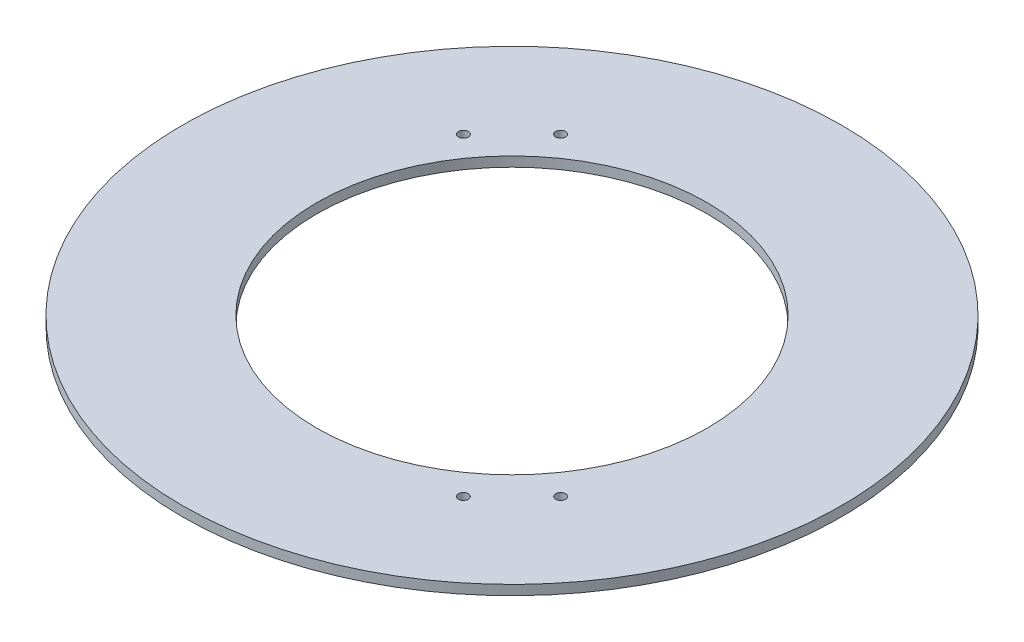
SolidWorks part; units mm, degrees
material "6061-T6 (SS)"
ref_plane "Front Plane" through (0, 0, 0) normal (0, 0, 1) x (1, 0, 0)
ref_plane "Top Plane" through (0, 0, 0) normal (0, 1, 0) x (1, 0, 0)
ref_plane "Right Plane" through (0, 0, 0) normal (1, 0, 0) x (0, 0, -1)
sketch "Sketch2" plane through (0, 0, 0) normal (0, 1, 0) x (1, 0, 0)
  line L0 (-135, 0) -> (135, 0) construction
  line L2 (0, 135) -> (0, -135) construction
  line L4 (-95.4594, 95.4594) -> (95.4594, -95.4594) construction
  line L5 (-54.3023, 74.2073) -> (-74.2073, 54.3023) construction
  line L6 (95.4594, 95.4594) -> (-95.4594, -95.4594) construction
  line L7 (74.2073, -54.3023) -> (54.3023, -74.2073) construction
  circle A0 centre (0, 0) radius 80
  circle A1 centre (0, 0) radius 135
  circle A6 centre (-74.2073, 54.3023) radius 2
  circle A7 centre (-54.3023, 74.2073) radius 2
  circle A8 centre (54.3023, -74.2073) radius 2
  circle A9 centre (74.2073, -54.3023) radius 2
  dimension "D1" = 160
  dimension "D2" = 270
  dimension "D3" = 181.74
  dimension "D7" = 4
  dimension "D6" = 45
  dimension "D8" = 45
  dimension "D9" = 28.15
extrude "Boss-Extrude1" add sketch "Sketch2" along normal blind 4
sketch "Sketch3" plane through (0, 4, 0) normal (0, 1, 0) x (1, 0, 0)
  line L0 (0, 135) -> (0, 80) construction
  line L1 (-107.5, 0) -> (-121.25, 0) construction
  line L2 (-121.25, 0) -> (-135, 0) construction
  line L3 (0, 0) -> (-54.3023, 74.2073) construction
  line L4 (0, 0) -> (-74.2073, 54.3023) construction
  line L5 (0, 0) -> (-95.4594, 95.4594) construction
  line L6 (-54.3023, 74.2073) -> (-74.2073, 54.3023) construction
  line L7 (0, 0) -> (95.4594, -95.4594) construction
  line L8 (0, 0) -> (95.4594, 95.4594) construction
  line L9 (0, 0) -> (-95.4594, -95.4594) construction
  circle A0 centre (0, 0) radius 107.5 construction
  circle A1 centre (0, 0) radius 135 construction
  circle A2 centre (0, 0) radius 80 construction
  circle A3 centre (0, 0) radius 135 construction
  circle A4 centre (0, 0) radius 121.25 construction
  point P10 (0, 107.5)
  point P15 (-64.2548, 64.2548)
